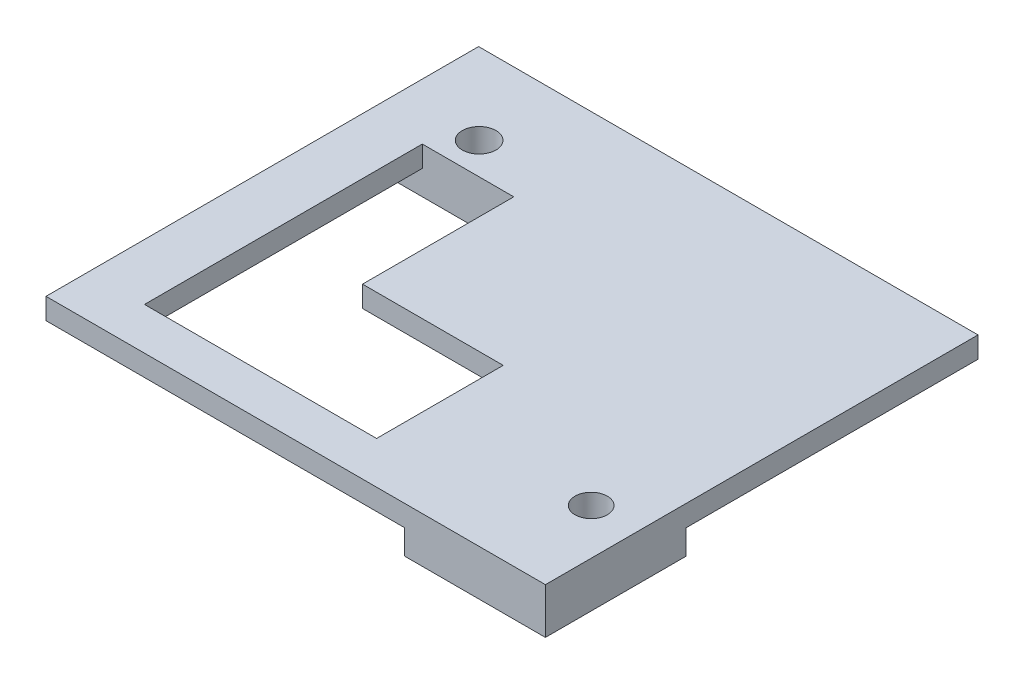
SolidWorks part; units mm, degrees
ref_plane "Front Plane" through (0, 0, 0) normal (0, 0, 1) x (1, 0, 0)
ref_plane "Top Plane" through (0, 0, 0) normal (0, 1, 0) x (1, 0, 0)
ref_plane "Right Plane" through (0, 0, 0) normal (1, 0, 0) x (0, 0, -1)
sketch "Sketch1" plane through (0, 0, 0) normal (0, 1, 0) x (1, 0, 0)
  line L1 (0, 0) -> (45.5, 0)
  line L2 (0, 0) -> (0, 30.75)
  line L3 (0, 30.75) -> (45.5, 30.75)
  line L4 (45.5, 0) -> (45.5, 30.75)
  dimension "D1" = 45.5
  dimension "D2" = 30.75
extrude "Boss-Extrude1" add sketch "Sketch1" along normal blind 1.5
sketch "Sketch2" plane through (0, 1.5, 0) normal (0, 1, 0) x (1, 0, 0)
  line L0 (30.5, 0) -> (30.5, 12)
  line L1 (0, 0) -> (45.5, 0) construction
  line L2 (30.5, 12) -> (20.5, 12)
  line L3 (10, 22.75) -> (10, 30.75)
  line L4 (45.5, 30.75) -> (0, 30.75) construction
  line L5 (45.5, 0) -> (45.5, 30.75) construction
  line L6 (20.5, 12) -> (20.5, 22.75)
  line L7 (20.5, 22.75) -> (10, 22.75)
  line L8 (0, 30.75) -> (0, 0) construction
  line L9 (10, 30.75) -> (0, 30.75)
  line L10 (0, 30.75) -> (0, 0)
  line L11 (0, 0) -> (30.5, 0)
  line L12 (14, 22.75) -> (14, 3)
  line L13 (14, 3) -> (30.5, 3)
  line L14 (10, 22.75) -> (10, 0)
  point P10 (45.5, 15.375)
  line M5 (0, 30.75) -> (0, 0)
  line M6 (0, 0) -> (45.5, 0)
  line M8 (45.5, 30.75) -> (0, 30.75)
  dimension "D1" = 12
  dimension "D2" = 15
  dimension "D3" = 8
  dimension "D4" = 25
  dimension "D5" = 10
  dimension "D6" = 14
  dimension "D7" = 3
sketch "Sketch3" plane through (0, 1.5, 0) normal (0, 1, 0) x (1, 0, 0)
  line L5 (45.5, 30.75) -> (0, 30.75) construction
  line L6 (45.5, 0) -> (35.5, 0)
  line L7 (45.5, 0) -> (45.5, 10)
  line L8 (45.5, 10) -> (35.5, 10)
  line L9 (35.5, 0) -> (35.5, 10)
  line L10 (12, 22.75) -> (20, 22.75)
  line L11 (12, 22.75) -> (12, 30.75)
  line L12 (12, 30.75) -> (20, 30.75)
  line L13 (20, 22.75) -> (20, 30.75)
  line L14 (0, 30.75) -> (0, 0) construction
  dimension "D1" = 20
  dimension "D2" = 8
  dimension "D3" = 10
  dimension "D4" = 10
  dimension "D5" = 12
extrude "Cut-Extrude1" cut sketch "Sketch2" against normal through all contours L14 L3 M8 M5 M6 | L12 L13 L0 L2 L6 L7
extrude "Boss-Extrude2" add sketch "Sketch3" against normal blind 3.25
sketch "Sketch4" plane through (0, -1.75, 0) normal (0, -1, 0) x (-1, 0, 0)
  line L0 (-45.5, 0) -> (-45.5, 10) construction
  line L1 (-35.5, 0) -> (-45.5, 0) construction
  line L3 (-12, 30.75) -> (-12, 22.75) construction
  line L4 (-20, 30.75) -> (-12, 30.75) construction
  circle A0 centre (-42.25, 6.5) radius 1.15
  circle A1 centre (-15.79, 25) radius 1.2
  dimension "D1" = 2.4
  dimension "D2" = 2.3
  dimension "D3" = 3.25
  dimension "D4" = 6.5
  dimension "D5" = 5.75
  dimension "D6" = 3.79
extrude "Cut-Extrude2" cut sketch "Sketch4" against normal through all
